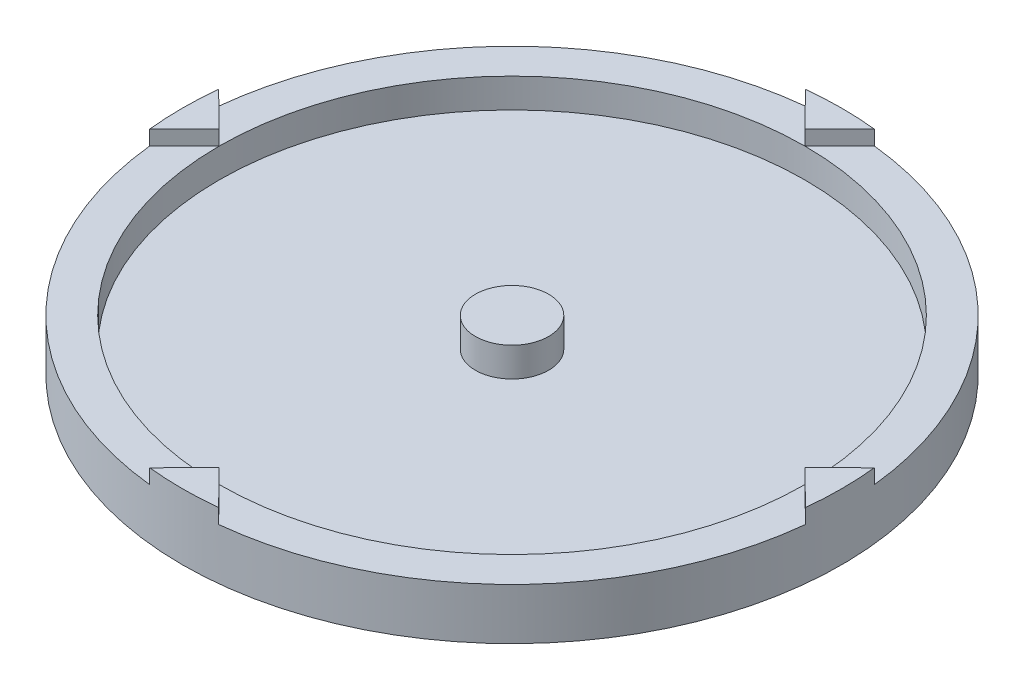
SolidWorks part; units mm, degrees
ref_plane "Front Plane" through (0, 0, 0) normal (0, 0, 1) x (1, 0, 0)
ref_plane "Top Plane" through (0, 0, 0) normal (0, 1, 0) x (1, 0, 0)
ref_plane "Right Plane" through (0, 0, 0) normal (1, 0, 0) x (0, 0, -1)
sketch "Sketch1" plane through (0, 0, 0) normal (0, 1, 0) x (1, 0, 0)
  circle A0 centre (0, 0) radius 45
  dimension "D1" = 90
extrude "Boss-Extrude1" add sketch "Sketch1" along normal blind 7
sketch "Sketch2" plane through (0, 7, 0) normal (0, 1, 0) x (1, 0, 0)
  circle A0 centre (0, 0) radius 40
  dimension "D1" = 80
extrude "Cut-Extrude1" cut sketch "Sketch2" against normal blind 4
sketch "Sketch3" plane through (0, 3, 0) normal (0, 1, 0) x (1, 0, 0)
  circle A0 centre (0, 0) radius 5
  dimension "D1" = 10
extrude "Boss-Extrude2" add sketch "Sketch3" along normal blind 4
sketch "Sketch4" plane through (0, 7, 0) normal (0, 1, 0) x (1, 0, 0)
  line L0 (0, 0) -> (0, 45) construction
  line L1 (0, 0) -> (0, -45) construction
  line L2 (0, 0) -> (45, 0) construction
  line L3 (0, 0) -> (-45, 0) construction
  line L4 (0, 0) -> (-4.7038, 44.7535) construction
  line L5 (0, 0) -> (4.7038, 44.7535) construction
  line L6 (0, 40) -> (-4.7038, 44.7535)
  line L7 (4.7038, 44.7535) -> (0, 40)
  circle A0 centre (0, 0) radius 45 construction
  circle A2 centre (0, 0) radius 40 construction
  arc A3 (-4.7038, 44.7535) -> (4.7038, 44.7535) centre (0, 0) cw
  dimension "D1" = 6
  dimension "D2" = 6
extrude "Boss-Extrude3" add sketch "Sketch4" along normal blind 2
pattern_circular "CirPattern1" count 4 over 360 about axis through (0, 0, 0) along (0, 1, 0) of "Boss-Extrude3"
sketch "Sketch5" plane through (0, 0, 0) normal (0, -1, 0) x (-1, 0, 0)
  line L0 (0, 0) -> (45, 0) construction
  line L1 (0, 0) -> (-45, 0) construction
  circle A0 centre (0, 0) radius 45 construction
  circle A1 centre (30, 0) radius 4.9
  dimension "D1" = 9.8
  dimension "D2" = 30
extrude "Boss-Extrude4" add sketch "Sketch5" along normal blind 8
mirror "Mirror1" about plane through (0, 0, 0) normal (1, 0, 0) of "Boss-Extrude4"
